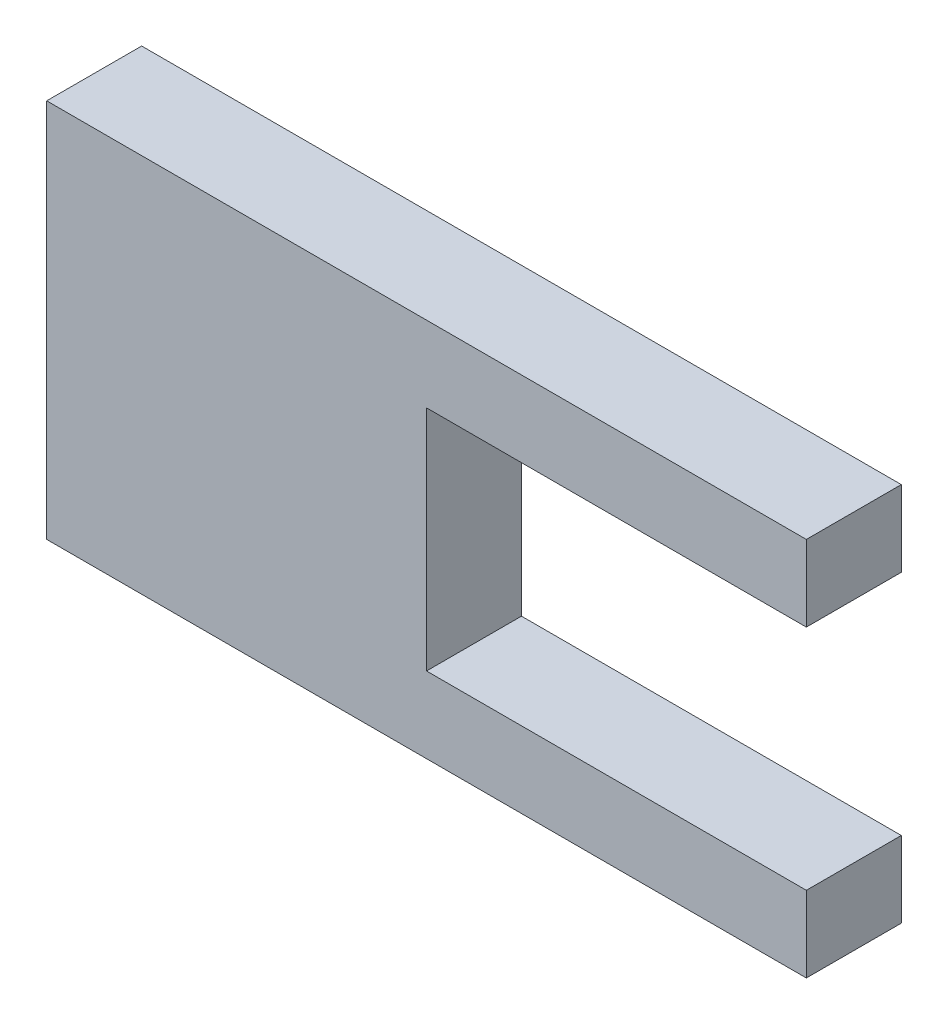
SolidWorks part; units mm, degrees
ref_plane "Front Plane" through (0, 0, 0) normal (1, 0, 0) x (0, 1, 0)
ref_plane "Top Plane" through (0, 0, 0) normal (0, 0, 1) x (0, 1, 0)
ref_plane "Right Plane" through (0, 0, 0) normal (0, 1, 0) x (-1, 0, 0)
sketch "Sketch2" plane through (0, 0, 0) normal (0, 0, 1) x (0, 1, 0)
  line L1 (-10, 10) -> (10, 10)
  line L2 (-10, 10) -> (-10, -10)
  line L3 (-6, -10) -> (6, -10)
  line L4 (10, 10) -> (10, -10)
  line L5 (-10, 10) -> (10, -10) construction
  line L6 (-10, -10) -> (10, 10) construction
  line L8 (-10, -10) -> (-10, -30)
  line L9 (-10, -30) -> (-6, -30)
  line L10 (-6, -10) -> (-6, -30)
  line L12 (10, -10) -> (10, -30)
  line L13 (10, -30) -> (6, -30)
  line L14 (6, -10) -> (6, -30)
  point P0 (0, 0)
  dimension "D1" = 20
  dimension "D2" = 20
  dimension "D3" = 20
  dimension "D4" = 4
  dimension "D5" = 20
  dimension "D6" = 4
extrude "Boss-Extrude1" add sketch "Sketch2" along normal blind 5
